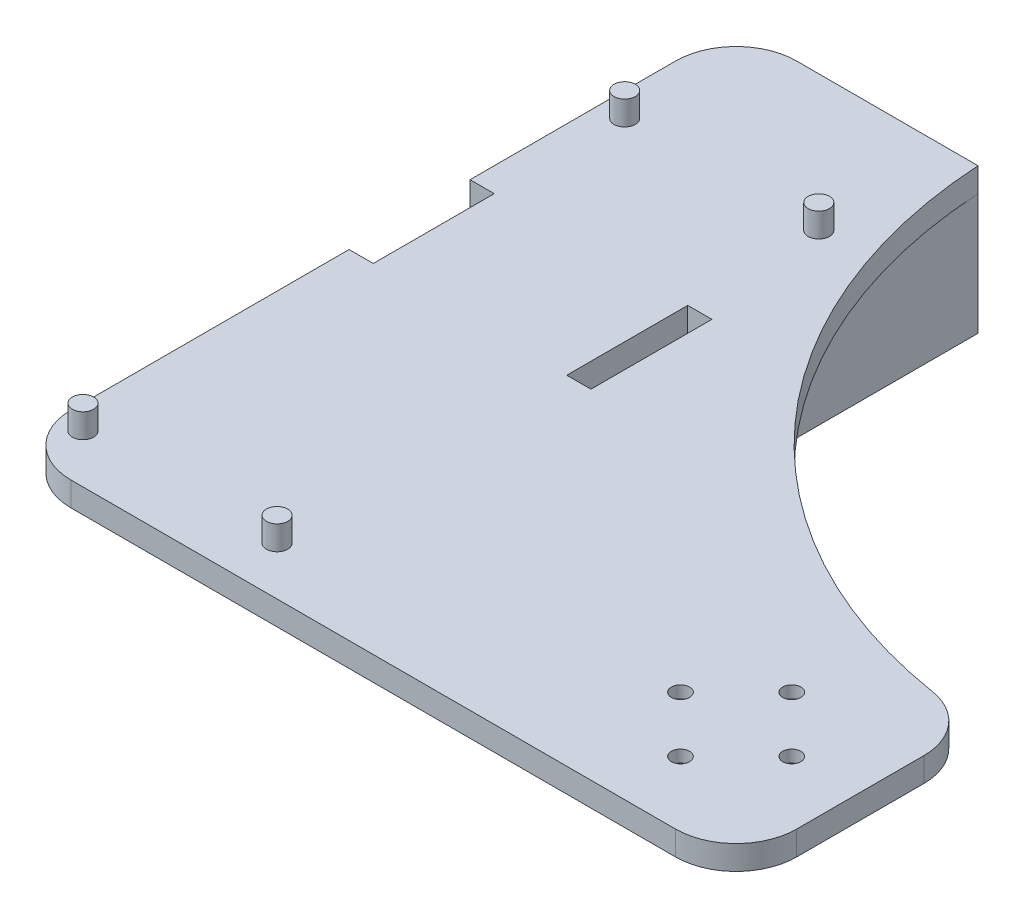
SolidWorks part; units mm, degrees
ref_plane "Front Plane" through (0, 0, 0) normal (0, 0, 1) x (1, 0, 0)
ref_plane "Top Plane" through (0, 0, 0) normal (0, 1, 0) x (1, 0, 0)
ref_plane "Right Plane" through (0, 0, 0) normal (1, 0, 0) x (0, 0, -1)
sketch "Sketch1" plane through (0, 0, 0) normal (0, 1, 0) x (1, 0, 0)
  line L0 (0, 0) -> (0, 76.2)
  line L1 (0, 0) -> (76.2, 0)
  line L2 (0, 76.2) -> (25.4, 76.2)
  line L3 (76.2, 0) -> (76.2, 25.4)
  circle A0 centre (63.5, 6.858) radius 0.9525
  circle A1 centre (57.658, 12.7) radius 0.9525
  circle A2 centre (63.5, 18.542) radius 0.9525
  circle A3 centre (69.342, 12.7) radius 0.9525
  arc A4 (25.4, 76.2) -> (76.2, 25.4) centre (79.375, 79.375) ccw
  point P3 (63.5, 12.7)
  point P18 (63.5, 12.7)
  dimension "D7" = 1.905
  dimension "D10" = 54.0683
  dimension "D1" = 76.2
  dimension "D2" = 76.2
  dimension "D3" = 25.4
  dimension "D4" = 25.4
  dimension "D5" = 12.7
  dimension "D6" = 12.7
  dimension "D8" = 5.842
  dimension "D9" = 4
extrude "Boss-Extrude1" add sketch "Sketch1" along normal blind 2.54
sketch "Sketch2" plane through (0, 0, 0) normal (0, -1, 0) x (1, 0, 0)
  line L0 (0, -76.2) -> (2.54, -76.2)
  line L1 (0, -76.2) -> (0, 0) construction
  line L2 (2.54, -76.2) -> (2.54, -50.8)
  line L3 (2.54, -50.8) -> (0, -50.8)
  line L5 (0, -50.8) -> (0, -76.2)
  line L6 (25.4, -76.2) -> (22.86, -76.2)
  line L7 (22.86, -76.2) -> (22.86, -50.8)
  line L8 (22.86, -50.8) -> (25.4, -50.8)
  line L9 (25.4, -50.8) -> (25.4, -76.2)
  line L11 (25.4, -76.2) -> (0, -76.2) construction
  dimension "D1" = 2.54
  dimension "D2" = 25.4
  dimension "D3" = 2.54
  dimension "D4" = 25.4
extrude "Boss-Extrude2" add sketch "Sketch2" along normal blind 12.7
fillet "Fillet2" radius 6.35 1 edges at (0, -5.08, -76.2)
fillet "Fillet3" radius 6.35 1 edges at (0, 1.27, 0)
fillet "Fillet4" radius 6.35 1 edges at (76.2, 1.27, 0)
fillet "Fillet5" radius 6.35 1 edges at (76.2, 1.27, -25.4)
sketch "Sketch3" plane through (0, 0, 0) normal (0, -1, 0) x (1, 0, 0)
  circle A0 centre (63.5, -6.858) radius 1.905
  circle A1 centre (69.342, -12.7) radius 1.905
  circle A2 centre (57.658, -12.7) radius 1.905
  circle A3 centre (63.5, -18.542) radius 1.905
  dimension "D1" = 3.81
  dimension "D2" = 3.81
  dimension "D3" = 3.81
  dimension "D4" = 3.81
extrude "Cut-Extrude1" cut sketch "Sketch3" against normal blind 1.27
sketch "Sketch4" plane through (0, 0, 0) normal (0, -1, 0) x (1, 0, 0)
  line L1 (22.86, -48.26) -> (25.4, -48.26)
  line L2 (22.86, -48.26) -> (22.86, -35.56)
  line L3 (22.86, -35.56) -> (25.4, -35.56)
  line L4 (25.4, -48.26) -> (25.4, -35.56)
  line L5 (2.54, -48.26) -> (0, -48.26)
  line L6 (2.54, -48.26) -> (2.54, -35.56)
  line L7 (2.54, -35.56) -> (0, -35.56)
  line L8 (0, -48.26) -> (0, -35.56)
  line L9 (2.54, -50.8) -> (0, -50.8) construction
  line L10 (25.4, -50.8) -> (22.86, -50.8) construction
  line L11 (0, -50.8) -> (0, -6.35) construction
  dimension "D1" = 2.54
  dimension "D2" = 12.7
  dimension "D3" = 12.7
  dimension "D4" = 2.54
  dimension "D6" = 2.54
  dimension "D7" = 0
  dimension "D8" = 2.54
extrude "Cut-Extrude2" cut sketch "Sketch4" against normal through all
sketch "Sketch5" plane through (0, 2.54, 0) normal (0, 1, 0) x (1, 0, 0)
  line L0 (6.35, 0) -> (69.85, 0) construction
  line L1 (0, 35.56) -> (0, 6.35) construction
  circle A0 centre (2.54, 5.08) radius 1.1176
  circle A1 centre (2.54, 61.9608) radius 1.1176
  circle A2 centre (22.921, 61.9608) radius 1.1176
  circle A3 centre (22.921, 5.08) radius 1.1176
  dimension "D1" = 2.2352
  dimension "D4" = 2.2352
  dimension "D7" = 2.2352
  dimension "D6" = 2.2352
  dimension "D2" = 5.08
  dimension "D3" = 2.54
  dimension "D5" = 56.8808
  dimension "D8" = 20.381
extrude "Boss-Extrude3" add sketch "Sketch5" along normal blind 2.54
